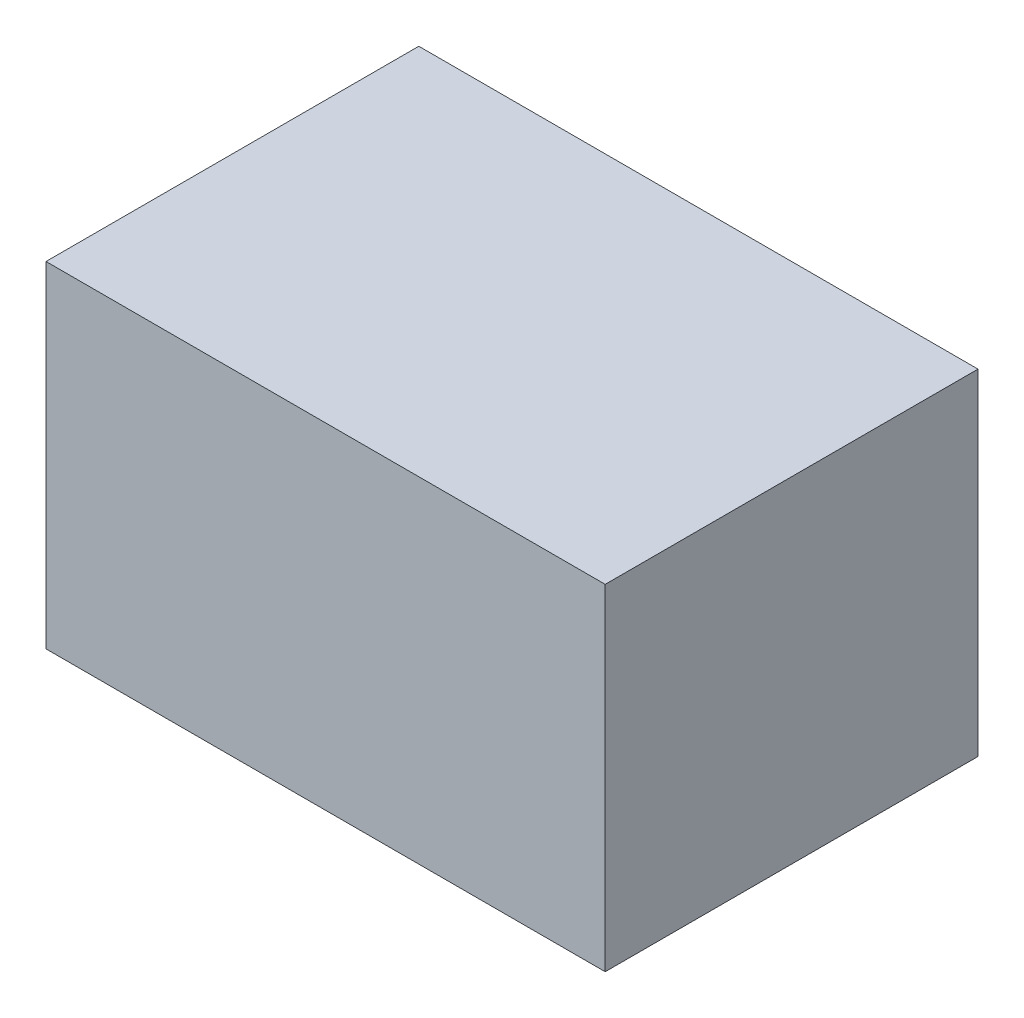
SolidWorks part; units mm, degrees
ref_plane "Спереди" through (0, 0, 0) normal (0, 0, 1) x (1, 0, 0)
ref_plane "Сверху" through (0, 0, 0) normal (0, 1, 0) x (1, 0, 0)
ref_plane "Справа" through (0, 0, 0) normal (1, 0, 0) x (0, 0, -1)
sketch "Sketch1" plane through (0, 0, 0) normal (0, 1, 0) x (1, 0, 0)
  line L1 (-15, -10) -> (15, -10)
  line L2 (-15, -10) -> (-15, 10)
  line L3 (-15, 10) -> (15, 10)
  line L4 (15, -10) -> (15, 10)
  line L5 (-15, -10) -> (15, 10) construction
  line L6 (-15, 10) -> (15, -10) construction
  point P0 (0, 0)
  dimension "D1" = 30
  dimension "D2" = 20
extrude "Boss-Extrude1" add sketch "Sketch1" along normal blind 18
